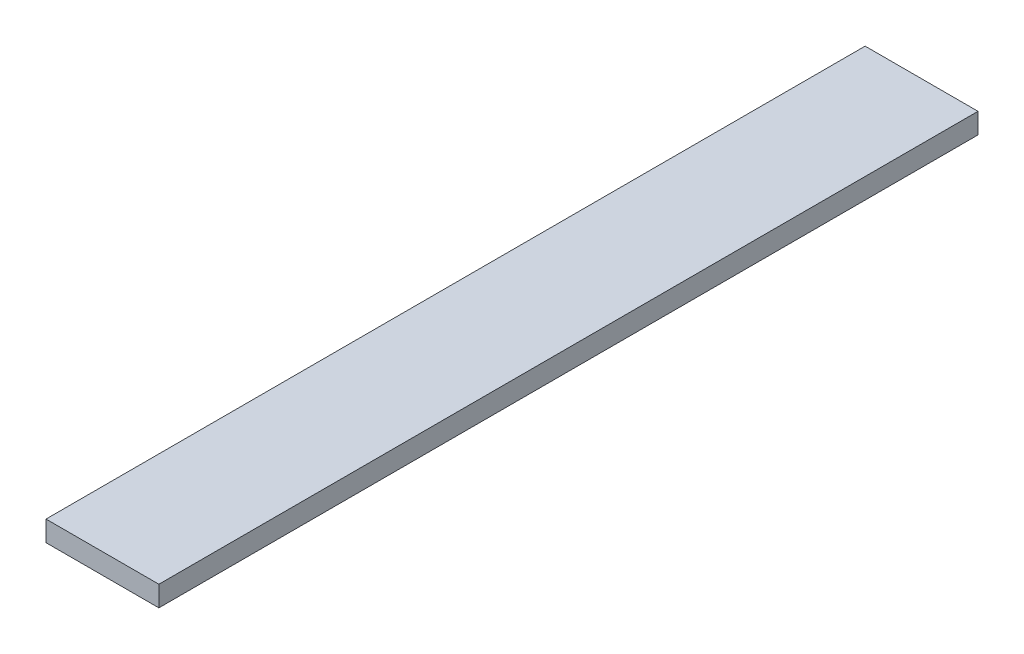
SolidWorks part; units mm, degrees
ref_plane "Front Plane" through (0, 0, 0) normal (0, 0, 1) x (1, 0, 0)
ref_plane "Top Plane" through (0, 0, 0) normal (0, 1, 0) x (1, 0, 0)
ref_plane "Right Plane" through (0, 0, 0) normal (1, 0, 0) x (0, 0, -1)
sketch "Sketch2" plane through (0, 0, 0) normal (0, 1, 0) x (1, 0, 0)
  line L0 (0, 0) -> (35, 0)
  line L1 (35, 0) -> (35, 254)
  line L2 (35, 254) -> (0, 254)
  line L3 (0, 254) -> (0, 0)
  dimension "D1" = 35
  dimension "D2" = 254
extrude "Boss-Extrude1" add sketch "Sketch2" along normal blind 6.35
equation "\"wall_thickness\"= 0.125in"
equation "\"base_thickness\"= 0.25in"
equation "\"D1@Boss-Extrude1\"=\"base_thickness\""
